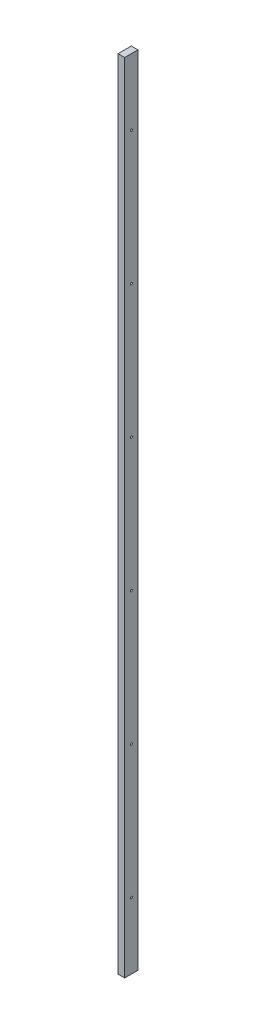
SolidWorks part; units mm, degrees
ref_plane "Спереди" through (0, 0, 0) normal (0, 0, 1) x (1, 0, 0)
ref_plane "Сверху" through (0, 0, 0) normal (0, 1, 0) x (1, 0, 0)
ref_plane "Справа" through (0, 0, 0) normal (1, 0, 0) x (0, 0, -1)
other "Configuration Table"
sketch "Эскиз1" plane through (0, 0, 0) normal (0, 1, 0) x (1, 0, 0)
  line L1 (12.5, 25) -> (-12.5, 25)
  line L2 (12.5, 25) -> (12.5, -25)
  line L3 (12.5, -25) -> (-12.5, -25)
  line L4 (-12.5, 25) -> (-12.5, -25)
  line L5 (12.5, 25) -> (-12.5, -25) construction
  line L6 (12.5, -25) -> (-12.5, 25) construction
  point P0 (0, 0)
extrude "Бобышка-Вытянуть1" add sketch "Эскиз1" along normal blind 3000
sketch "Эскиз2" plane through (12.5, 0, 0) normal (1, 0, 0) x (0, 0, -1)
  circle A0 centre (0, 250) radius 4
  circle A1 centre (0, 750) radius 4
  circle A2 centre (0, 1250) radius 4
  circle A3 centre (0, 1750) radius 4
  circle A4 centre (0, 2750) radius 4
  circle A5 centre (0, 2250) radius 4
extrude "Вырез-Вытянуть1" cut sketch "Эскиз2" against normal blind 100
